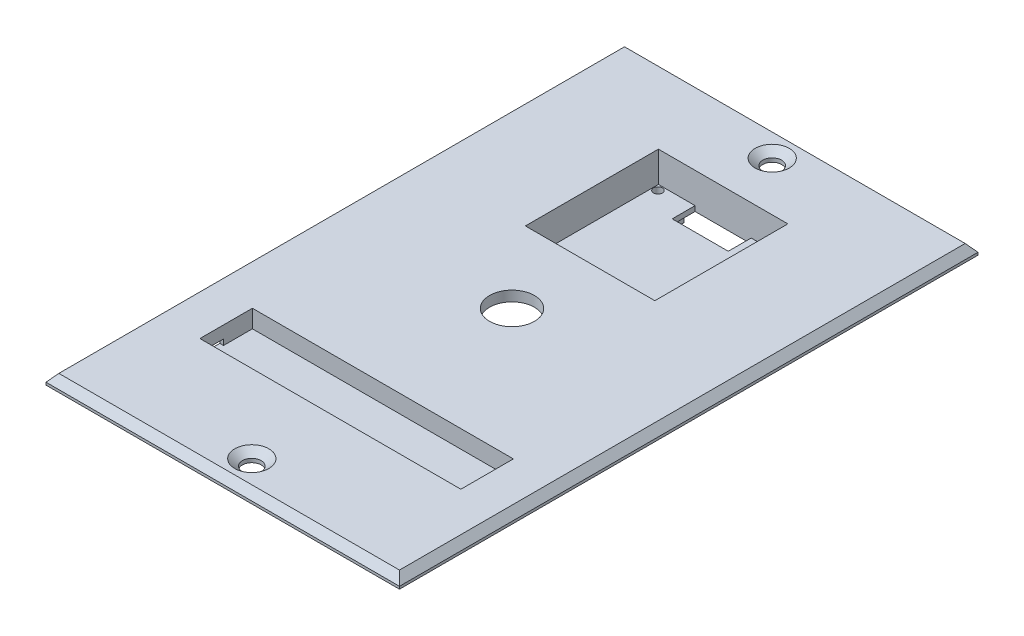
SolidWorks part; units mm, degrees
ref_plane "Front Plane" through (0, 0, 0) normal (0, 0, 1) x (1, 0, 0)
ref_plane "Top Plane" through (0, 0, 0) normal (0, 1, 0) x (1, 0, 0)
ref_plane "Right Plane" through (0, 0, 0) normal (1, 0, 0) x (0, 0, -1)
sketch "Sketch2" plane through (0, 0, 0) normal (0, 1, 0) x (1, 0, 0)
  line L0 (0, 56.75) -> (0, -56.75) construction
  line L1 (-34.675, 56.75) -> (34.675, 56.75)
  line L2 (-34.675, 56.75) -> (-34.675, -56.75)
  line L3 (-34.675, -56.75) -> (34.675, -56.75)
  line L4 (34.675, 56.75) -> (34.675, -56.75)
  line L5 (-34.675, 56.75) -> (34.675, -56.75) construction
  line L6 (-34.675, -56.75) -> (34.675, 56.75) construction
  line L7 (-34.675, 0) -> (34.675, 0) construction
  circle A0 centre (0, 51.0505) radius 1.85
  circle A1 centre (0, -51.0505) radius 1.85
  point P1 (0, 0)
  dimension "D3" = 3.7
  dimension "D1" = 69.35
  dimension "D2" = 113.5
extrude "Boss-Extrude3" add sketch "Sketch2" along normal blind 2
sketch "Sketch4" plane through (0, 2, 0) normal (0, 1, 0) x (1, 0, 0)
  line L0 (-34.675, 28.375) -> (34.675, 28.375) construction
  line L1 (-34.675, 56.75) -> (-34.675, -56.75) construction
  line L2 (34.675, -56.75) -> (34.675, 56.75) construction
  line L3 (34.675, 56.75) -> (-34.675, 56.75) construction
  line L4 (-34.675, 0) -> (34.675, 0) construction
  line L5 (-34.675, -28.375) -> (34.675, -28.375) construction
  line L6 (0, 56.75) -> (0, -56.75) construction
  line L7 (-34.675, -56.75) -> (34.675, -56.75) construction
  line L9 (-12.7, 41.425) -> (12.7, 41.425)
  line L10 (-12.7, 41.425) -> (-12.7, 15.325)
  line L11 (-12.7, 15.325) -> (12.7, 15.325)
  line L12 (12.7, 41.425) -> (12.7, 15.325)
  line L13 (-12.7, 41.425) -> (12.7, 15.325) construction
  line L14 (-12.7, 15.325) -> (12.7, 41.425) construction
  line L15 (-14.8247, 44.2528) -> (14.8247, 44.2528)
  line L16 (-14.8247, 44.2528) -> (-14.8247, 12.4972)
  line L17 (-14.8247, 12.4972) -> (14.8247, 12.4972)
  line L18 (14.8247, 44.2528) -> (14.8247, 12.4972)
  line L19 (-14.8247, 44.2528) -> (14.8247, 12.4972) construction
  line L20 (-14.8247, 12.4972) -> (14.8247, 44.2528) construction
  circle A0 centre (0, 0) radius 4.4
  point P20 (0, 28.375)
  point P24 (0, 28.375)
  dimension "D2" = 8.8
  dimension "D1" = 28.375
  dimension "D3" = 26.1
  dimension "D4" = 25.4
extrude "Cut-Extrude7" cut sketch "Sketch4" against normal blind 7.5 contours L10 L9 L12 L11
sketch "Sketch16" plane through (0, 0, 0) normal (0, -1, 0) x (-1, 0, 0)
  line L1 (-14.8231, 42.9785) -> (14.591, 42.9785)
  line L2 (-14.8231, 42.9785) -> (-14.8231, 13.4882)
  line L3 (-14.8231, 13.4882) -> (14.591, 13.4882)
  line L4 (14.591, 42.9785) -> (14.591, 13.4882)
extrude "Boss-Extrude18" add sketch "Sketch16" along normal blind 5
sketch "Sketch17" plane through (0, 0, 0) normal (0, 1, 0) x (1, 0, 0)
  line L1 (-12.7, 41.425) -> (12.7, 41.425)
  line L2 (-12.7, 41.425) -> (-12.7, 15.325)
  line L3 (-12.7, 15.325) -> (12.7, 15.325)
  line L4 (12.7, 41.425) -> (12.7, 15.325)
extrude "Cut-Extrude8" cut sketch "Sketch17" against normal blind 4
sketch "Sketch18" plane through (0, -4, 0) normal (0, 1, 0) x (1, 0, 0)
  line L0 (0, 41.425) -> (0, 15.325) construction
  line L1 (-12.7, 41.425) -> (-7.7, 41.425)
  line L2 (-12.7, 41.425) -> (-12.7, 36.425)
  line L3 (-12.7, 36.425) -> (-7.7, 36.425)
  line L4 (-7.7, 41.425) -> (-7.7, 36.425)
  line L5 (12.7, 41.425) -> (-12.7, 41.425) construction
  line L6 (-12.7, 15.325) -> (12.7, 15.325) construction
  line L7 (-12.7, 28.375) -> (12.7, 28.375) construction
  line L8 (-12.7, 41.425) -> (-12.7, 15.325) construction
  line L9 (12.7, 15.325) -> (12.7, 41.425) construction
  line L10 (12.7, 36.425) -> (7.7, 36.425)
  line L11 (7.7, 41.425) -> (7.7, 36.425)
  line L12 (12.7, 41.425) -> (7.7, 41.425)
  line L13 (12.7, 41.425) -> (12.7, 36.425)
  line L14 (12.7, 15.325) -> (12.7, 20.325)
  line L15 (12.7, 15.325) -> (7.7, 15.325)
  line L16 (7.7, 15.325) -> (7.7, 20.325)
  line L17 (12.7, 20.325) -> (7.7, 20.325)
  line L18 (-12.7, 20.325) -> (-7.7, 20.325)
  line L19 (-7.7, 15.325) -> (-7.7, 20.325)
  line L20 (-12.7, 15.325) -> (-7.7, 15.325)
  line L21 (-12.7, 15.325) -> (-12.7, 20.325)
  dimension "D1" = 5
  dimension "D2" = 5
extrude "Boss-Extrude24" add sketch "Sketch18" against normal blind 4
sketch "Sketch20" plane through (0, -8, 0) normal (0, -1, 0) x (-1, 0, 0)
  circle A0 centre (-11.66, 40.3691) radius 0.875
  circle A1 centre (11.7256, 40.3614) radius 0.875
  circle A2 centre (11.7256, 16.6577) radius 0.875
  circle A3 centre (-11.66, 16.6577) radius 0.875
extrude "Cut-Extrude10" cut sketch "Sketch20" against normal blind 4
sketch "Sketch24" plane through (0, -4, 0) normal (0, 1, 0) x (1, 0, 0)
  line L0 (-12.7, 39.175) -> (12.7, 39.175) construction
  line L1 (-12.7, 41.425) -> (-12.7, 15.325) construction
  line L2 (12.7, 15.325) -> (12.7, 41.425) construction
  line L3 (12.7, 41.425) -> (-12.7, 41.425) construction
  line L4 (-5.5, 36.925) -> (5.5, 36.925)
  line L5 (-5.5, 36.925) -> (-5.5, 41.425)
  line L6 (-5.5, 41.425) -> (5.5, 41.425)
  line L7 (5.5, 36.925) -> (5.5, 41.425)
  line L8 (-5.5, 36.925) -> (5.5, 41.425) construction
  line L9 (-5.5, 41.425) -> (5.5, 36.925) construction
  point P6 (0, 39.175)
  dimension "D1" = 11
  dimension "D2" = 4.5
extrude "Cut-Extrude11" cut sketch "Sketch24" against normal blind 4
chamfer "Chamfer1" distance 1.5 angle 40 4 edges at (0, 2, 56.75) (34.675, 2, 0) (0, 2, -56.75) (-34.675, 2, 0)
sketch "Sketch25" plane through (0, 2, 0) normal (0, 1, 0) x (1, 0, 0)
  line L0 (-33.4164, 0) -> (33.4164, 0)
  line L1 (-33.4164, 55.4914) -> (-33.4164, -55.4914) construction
  line L2 (33.4164, -55.4914) -> (33.4164, 55.4914) construction
  circle A0 centre (0, 0) radius 4.4
  dimension "D1" = 8.8
extrude "Cut-Extrude12" cut sketch "Sketch25" against normal blind 4 contours A0
sketch "Sketch26" plane through (0, 2, 0) normal (0, 1, 0) x (1, 0, 0)
  line L3 (-25.496, -25.4348) -> (25.704, -25.4348)
  line L5 (-25.496, -25.4348) -> (-25.496, -35.7348)
  line L6 (-25.496, -35.7348) -> (25.704, -35.7348)
  line L7 (25.704, -25.4348) -> (25.704, -35.7348)
  line L8 (-25.496, -25.4348) -> (25.704, -35.7348) construction
  line L9 (-25.496, -35.7348) -> (25.704, -25.4348) construction
  point P0 (0.104, -30.5848)
extrude "Cut-Extrude13" cut sketch "Sketch26" against normal blind 4 contours L5 L3 L7 L6
sketch "Sketch27" plane through (0, 0, 0) normal (0, -1, 0) x (-1, 0, 0)
  line L1 (26.2239, -36.3756) -> (-26.4281, -36.3756)
  line L2 (26.2239, -36.3756) -> (26.2239, -24.715)
  line L3 (26.2239, -24.715) -> (-26.4281, -24.715)
  line L4 (-26.4281, -36.3756) -> (-26.4281, -24.715)
extrude "Boss-Extrude30" add sketch "Sketch27" along normal blind 3 contours L2 L1 L4 L3
sketch "Sketch30" plane through (0, 0, 0) normal (0, 1, 0) x (1, 0, 0)
  line L1 (-25.496, -25.4348) -> (25.704, -25.4348)
  line L2 (-25.496, -25.4348) -> (-25.496, -35.7348)
  line L3 (-25.496, -35.7348) -> (25.704, -35.7348)
  line L4 (25.704, -25.4348) -> (25.704, -35.7348)
extrude "Cut-Extrude14" cut sketch "Sketch30" against normal blind 3
sketch "Sketch31" plane through (0, -3, 0) normal (0, -1, 0) x (-1, 0, 0)
  line L1 (25.496, -35.7348) -> (-25.704, -35.7348)
  line L2 (25.496, -35.7348) -> (25.496, -25.4348)
  line L3 (25.496, -25.4348) -> (-25.704, -25.4348)
  line L4 (-25.704, -35.7348) -> (-25.704, -25.4348)
extrude "Boss-Extrude31" add sketch "Sketch31" against normal blind 1.5
sketch "Sketch32" plane through (26.4281, 0, 0) normal (1, 0, 0) x (0, 0, -1)
  line L1 (-36.1974, -0.1859) -> (-24.9479, -0.1859)
  line L2 (-36.1974, -0.1859) -> (-36.1974, -2.7896)
  line L3 (-36.1974, -2.7896) -> (-24.9479, -2.7896)
  line L4 (-24.9479, -0.1859) -> (-24.9479, -2.7896)
extrude "Cut-Extrude15" cut sketch "Sketch32" against normal blind 1.5
sketch "Sketch33" plane through (0, -2.7896, 0) normal (0, 1, 0) x (1, 0, 0)
  line L1 (24.9281, -36.1974) -> (26.4281, -36.1974)
  line L2 (24.9281, -36.1974) -> (24.9281, -24.9479)
  line L3 (24.9281, -24.9479) -> (26.4281, -24.9479)
  line L4 (26.4281, -36.1974) -> (26.4281, -24.9479)
extrude "Cut-Extrude16" cut sketch "Sketch33" against normal blind 1.5
sketch "Sketch34" plane through (-26.2239, 0, 0) normal (-1, 0, 0) x (0, 0, 1)
  circle A0 centre (34.6222, -1.3779) radius 0.9911
extrude "Cut-Extrude17" cut sketch "Sketch34" against normal blind 1.5
sketch "Sketch35" plane through (-26.2239, 0, 0) normal (-1, 0, 0) x (0, 0, 1)
  line L1 (35.6058, -1.5) -> (31.1081, -1.5)
  line L2 (35.6058, -1.5) -> (35.6058, -0.3869)
  line L3 (35.6058, -0.3869) -> (31.1081, -0.3869)
  line L4 (31.1081, -1.5) -> (31.1081, -0.3869)
extrude "Cut-Extrude18" cut sketch "Sketch35" against normal blind 1.5
sketch "Sketch36" plane through (0, 0, 0) normal (0, -1, 0) x (-1, 0, 0)
  line L1 (31.0604, -23.2953) -> (-31.2173, -23.2953)
  line L2 (31.0604, -23.2953) -> (31.0604, -7.4514)
  line L3 (31.0604, -7.4514) -> (-31.2173, -7.4514)
  line L4 (-31.2173, -23.2953) -> (-31.2173, -7.4514)
extrude "Cut-Extrude19" cut sketch "Sketch36" against normal blind 0.5
sketch "Sketch37" plane through (0, 0, 0) normal (0, -1, 0) x (-1, 0, 0)
  line L1 (-30.5898, 52.4733) -> (-16.7852, 52.4733)
  line L2 (-30.5898, 52.4733) -> (-30.5898, 12.9418)
  line L3 (-30.5898, 12.9418) -> (-16.7852, 12.9418)
  line L4 (-16.7852, 52.4733) -> (-16.7852, 12.9418)
extrude "Cut-Extrude22" cut sketch "Sketch37" against normal blind 0.5
chamfer "Chamfer2" distance 1.5 angle 40 1 edges at (0, 2, 49.2005)
chamfer "Chamfer3" distance 1.5 angle 40 1 edges at (0, 2, -49.2005)
sketch "Sketch42" plane through (0, -1.5, 0) normal (0, 1, 0) x (1, 0, 0)
  circle A0 centre (-12.996, -33.2348) radius 0.875
  circle A1 centre (11.754, -33.2348) radius 0.875
extrude "Cut-Extrude23" cut sketch "Sketch42" against normal through all both and the other way through all
